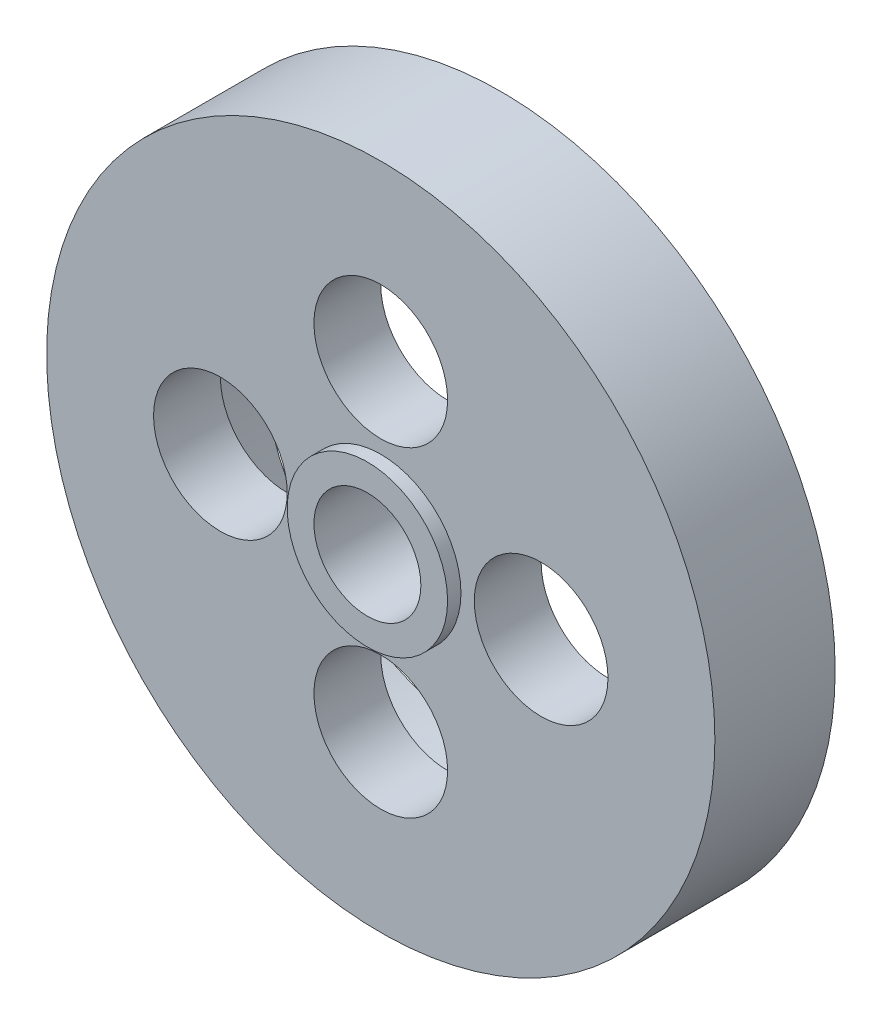
SolidWorks part; units mm, degrees
ref_plane "Front Plane" through (0, 0, 0) normal (0, 0, 1) x (1, 0, 0)
ref_plane "Top Plane" through (0, 0, 0) normal (0, 1, 0) x (1, 0, 0)
ref_plane "Right Plane" through (0, 0, 0) normal (1, 0, 0) x (0, 0, -1)
sketch "Sketch1" plane through (0, 0, 0) normal (0, 0, 1) x (1, 0, 0)
  circle A0 centre (0, 0) radius 25
  circle A1 centre (0, 0) radius 12 construction
  circle A2 centre (0, 12) radius 5
  circle A3 centre (12, 0) radius 5
  circle A4 centre (0, -12) radius 5
  circle A5 centre (-12, 0) radius 5
  circle A6 centre (0, 0) radius 4
  point P15 (0, 0)
  dimension "D1" = 50
  dimension "D2" = 24
  dimension "D3" = 10
  dimension "D5" = 8
  dimension "D6" = 12
  dimension "D4" = 4
extrude "Boss-Extrude1" add sketch "Sketch1" along normal blind 9
sketch "Sketch2" plane through (0, 0, 0) normal (0, 0, -1) x (-1, 0, 0)
  circle A0 centre (0, 0) radius 18
  dimension "D1" = 36
extrude "Cut-Extrude1" cut sketch "Sketch2" against normal blind 4
sketch "Sketch3" plane through (0, 0, 9) normal (0, 0, 1) x (1, 0, 0)
  circle A0 centre (0, 0) radius 6
  circle A1 centre (0, 0) radius 4 construction
  circle A2 centre (0, 0) radius 4
  dimension "D1" = 12
extrude "Boss-Extrude2" add sketch "Sketch3" along normal blind 1
